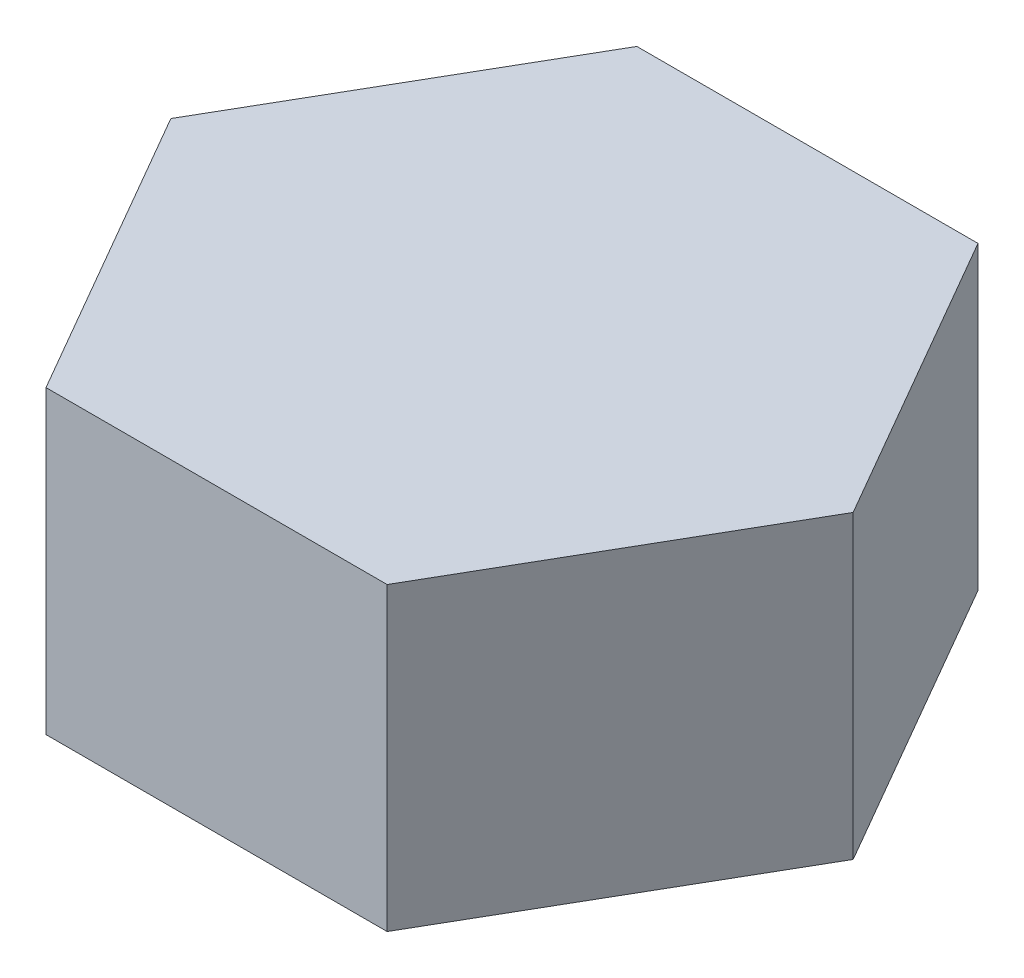
SolidWorks part; units mm, degrees
ref_plane "Front Plane" through (0, 0, 0) normal (0, 0, 1) x (1, 0, 0)
ref_plane "Top Plane" through (0, 0, 0) normal (0, 1, 0) x (1, 0, 0)
ref_plane "Right Plane" through (0, 0, 0) normal (1, 0, 0) x (0, 0, -1)
sketch "Sketch1" plane through (0, 0, 0) normal (0, 1, 0) x (1, 0, 0)
  line L0 (-3.1786, -5.5055) -> (-6.3571, 0)
  line L1 (-6.3571, 0) -> (-3.1786, 5.5054)
  line L2 (-3.1786, 5.5054) -> (3.1786, 5.5055)
  line L3 (3.1786, 5.5055) -> (6.3571, 0)
  line L4 (6.3571, 0) -> (3.1786, -5.5054)
  line L5 (3.1786, -5.5054) -> (-3.1786, -5.5055)
  circle A0 centre (0, 0) radius 5.5054 construction
  point P5 (0, -5.5055)
  point P10 (-4.7679, -2.7527)
  point P11 (-4.7679, 2.7527)
  point P12 (0, 5.5054)
  point P13 (4.7679, 2.7527)
  point P14 (4.7679, -2.7527)
  point P15 (-1.5594, 5.7623)
  point P16 (-5.4132, 1.5618)
  point P17 (-3.1865, 5.5009)
  point P18 (0, 0)
  dimension "D1" = 11.0109
extrude "Boss-Extrude1" add sketch "Sketch1" along normal blind 5.6007
